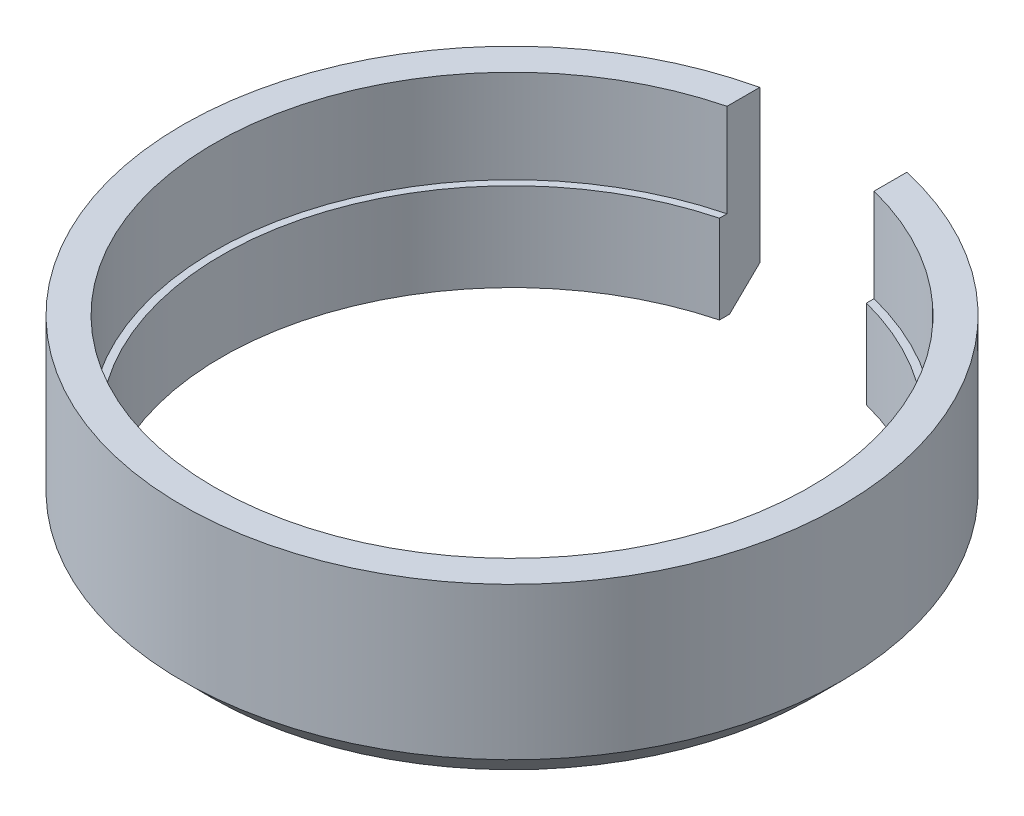
SolidWorks part; units mm, degrees
ref_plane "Front" through (0, 0, 0) normal (0, 0, 1) x (1, 0, 0)
ref_plane "Top" through (0, 0, 0) normal (0, 1, 0) x (1, 0, 0)
ref_plane "Right" through (0, 0, 0) normal (1, 0, 0) x (0, 0, -1)
sketch "Эскиз1" plane through (0, 0, 0) normal (0, 0, 1) x (1, 0, 0)
  line L0 (0, 0) -> (0, 7.4) construction
  line L1 (-11.85, 0) -> (-13.45, 0)
  line L2 (-13.45, 0) -> (-13.45, 7.4)
  line L3 (-13.45, 7.4) -> (-12.15, 7.4)
  line L4 (-12.15, 7.4) -> (-12.15, 3.6)
  line L5 (-12.15, 3.6) -> (-11.85, 3.6)
  line L6 (-11.85, 3.6) -> (-11.85, 0)
  dimension "D1" = 7.4
  dimension "D2" = 26.9
  dimension "D3" = 24.3
  dimension "D4" = 3.8
  dimension "D5" = 0.3
revolve "Повернуть1" add sketch "Эскиз1" angle 360 about L0
chamfer "Фаска1" distance 1.2 angle 45 1 edges at (0, 0, -13.45)
sketch "Эскиз2" plane through (0, 7.4, 0) normal (0, 1, 0) x (1, 0, 0)
  line L1 (-3, 17) -> (3, 17)
  line L2 (-3, 17) -> (-3, 7)
  line L3 (-3, 7) -> (3, 7)
  line L4 (3, 17) -> (3, 7)
  dimension "D1" = 6
  dimension "D2" = 3
  dimension "D3" = 7
  dimension "D4" = 10
extrude "Вырез-Вытянуть1" cut sketch "Эскиз2" against normal up to next
